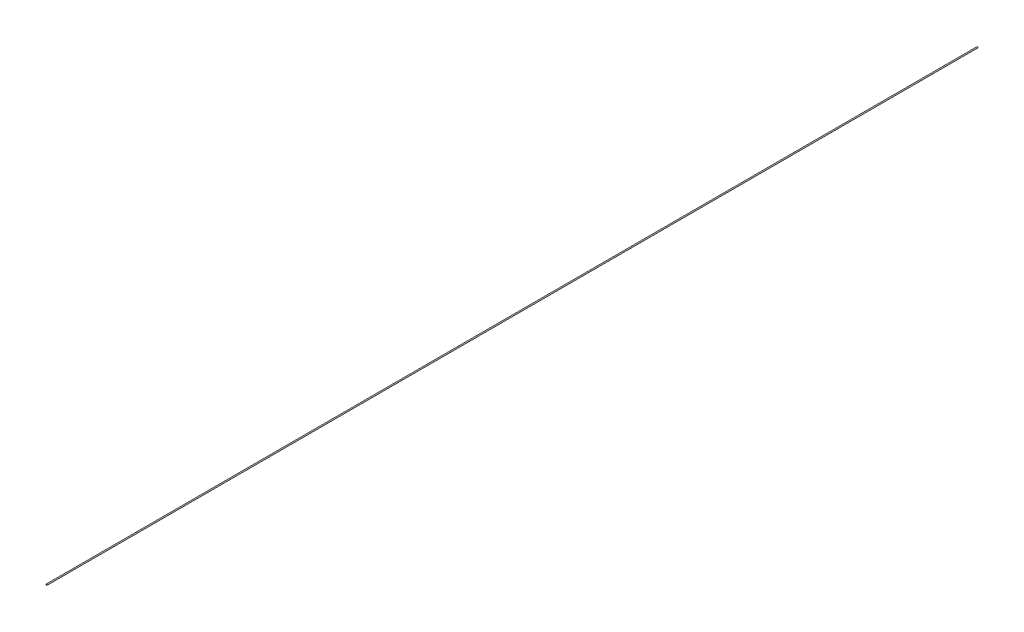
SolidWorks part; units mm, degrees
ref_plane "前视基准面" through (0, 0, 0) normal (0, 0, 1) x (1, 0, 0)
ref_plane "上视基准面" through (0, 0, 0) normal (0, 1, 0) x (1, 0, 0)
ref_plane "右视基准面" through (0, 0, 0) normal (1, 0, 0) x (0, 0, -1)
sketch "草图2" plane through (0, 0, 0) normal (0, 0, 1) x (1, 0, 0)
  circle A0 centre (0, 0) radius 0.6
extrude "凸台-拉伸1" add sketch "草图2" along normal blind 1012.19
